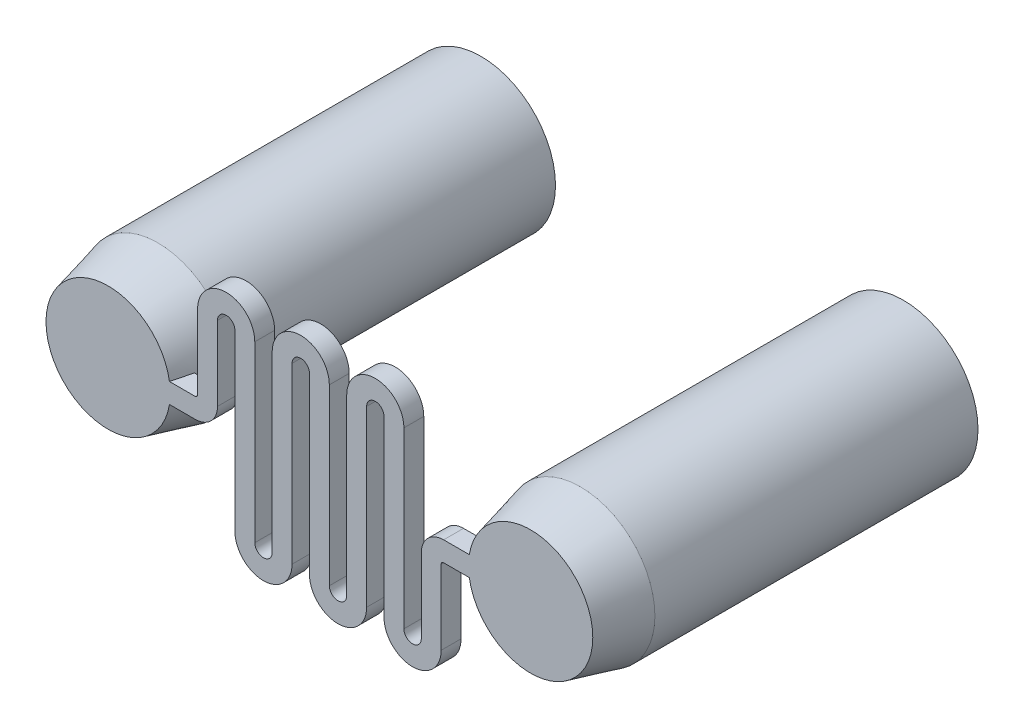
SolidWorks part; units mm, degrees
ref_plane "Front Plane" through (0, 0, 0) normal (0, 0, 1) x (1, 0, 0)
ref_plane "Top Plane" through (0, 0, 0) normal (0, 1, 0) x (1, 0, 0)
ref_plane "Right Plane" through (0, 0, 0) normal (1, 0, 0) x (0, 0, -1)
sketch "Sketch2" plane through (0, 0, 0) normal (0, 0, 1) x (1, 0, 0)
  line L3 (-20.5, -0.8) -> (-13.5, -0.8)
  line L6 (-11.7, 1) -> (-11.7, 7)
  line L9 (-10.3, 7) -> (-10.3, 0)
  line L12 (-10.3, 0) -> (-10.3, -7)
  line L15 (-5.7, -7) -> (-5.7, 0)
  line L18 (-5.7, 0) -> (-5.7, 7)
  line L21 (-4.3, 7) -> (-4.3, 0)
  line L22 (-4.3, 0) -> (-4.3, -7)
  line L23 (0.3, -7) -> (0.3, 0)
  line L24 (0.3, 0) -> (0.3, 7)
  line L25 (1.7, 7) -> (1.7, 0)
  line L26 (1.7, 0) -> (1.7, -7)
  line L27 (6.3, -7) -> (6.3, -1)
  line L28 (6.5, -0.8) -> (13.5, -0.8)
  line L29 (-20.5, 0.8) -> (-13.5, 0.8)
  line L30 (-13.3, 1) -> (-13.3, 7)
  line L31 (-8.7, 7) -> (-8.7, 0)
  line L32 (-8.7, 0) -> (-8.7, -7)
  line L33 (-7.3, -7) -> (-7.3, 0)
  line L34 (-7.3, 0) -> (-7.3, 7)
  line L35 (-2.7, 7) -> (-2.7, 0)
  line L36 (-2.7, 0) -> (-2.7, -7)
  line L37 (-1.3, -7) -> (-1.3, 0)
  line L38 (-1.3, 0) -> (-1.3, 7)
  line L39 (3.3, 7) -> (3.3, 0)
  line L40 (3.3, 0) -> (3.3, -7)
  line L41 (4.7, -7) -> (4.7, -1)
  line L42 (6.5, 0.8) -> (13.5, 0.8)
  arc A8 (-11.7, 1) -> (-13.5, -0.8) centre (-13.5, 1) cw
  arc A9 (-11.7, 7) -> (-10.3, 7) centre (-11, 7) cw
  arc A10 (-10.3, -7) -> (-5.7, -7) centre (-8, -7) ccw
  arc A11 (-5.7, 7) -> (-4.3, 7) centre (-5, 7) cw
  arc A12 (-4.3, -7) -> (0.3, -7) centre (-2, -7) ccw
  arc A13 (0.3, 7) -> (1.7, 7) centre (1, 7) cw
  arc A14 (1.7, -7) -> (6.3, -7) centre (4, -7) ccw
  arc A15 (6.3, -1) -> (6.5, -0.8) centre (6.5, -1) cw
  arc A16 (-13.3, 1) -> (-13.5, 0.8) centre (-13.5, 1) cw
  arc A17 (-13.3, 7) -> (-8.7, 7) centre (-11, 7) cw
  arc A18 (-8.7, -7) -> (-7.3, -7) centre (-8, -7) ccw
  arc A19 (-7.3, 7) -> (-2.7, 7) centre (-5, 7) cw
  arc A20 (-2.7, -7) -> (-1.3, -7) centre (-2, -7) ccw
  arc A21 (-1.3, 7) -> (3.3, 7) centre (1, 7) cw
  arc A22 (3.3, -7) -> (4.7, -7) centre (4, -7) ccw
  arc A23 (4.7, -1) -> (6.5, 0.8) centre (6.5, -1) cw
  arc A24 (-20.5, 0.8) -> (-20.5, -0.8) centre (-20.5, 0) ccw
  arc A25 (13.5, -0.8) -> (13.5, 0.8) centre (13.5, 0) ccw
  point P4 (0, 0)
  point P32 (5.5, 0)
  point P35 (-12.5, 0)
  dimension "D1" = 8
  dimension "D14" = 8
extrude "Boss-Extrude1" add sketch "Sketch2" along normal blind 1.6
ref_plane "Plane1" through (0, 0, 0) normal (0, 1, 0) x (1, 0, 0)
ref_plane "Plane2" through (0, 0, 0) normal (0, 1, 0) x (1, 0, 0)
sketch "Sketch3" plane through (0, 0, 0) normal (0, 1, 0) x (1, 0, 0)
  line L0 (-20.5, -1.6) -> (-25.5, -1.6)
  line L2 (-20.5, -1.6) -> (-20.5, 28.4)
  line L3 (-20.5, 28.4) -> (-26.5, 28.4)
  line L4 (-26.5, 28.4) -> (-26.5, 2.4)
  line L5 (-26.5, 2.4) -> (-25.5, -1.6)
  dimension "D1" = 30
  dimension "D2" = 5
  dimension "D4" = 6
revolve "Revolve1" add sketch "Sketch3" angle 360 about L2
sketch "Sketch4" plane through (0, 0, 0) normal (0, 1, 0) x (1, 0, 0)
  line L0 (13.5, -1.6) -> (18.5, -1.6)
  line L2 (13.5, -1.6) -> (13.5, 28.4)
  line L3 (13.5, 28.4) -> (19.5, 28.4)
  line L4 (19.5, 28.4) -> (19.5, 2.4)
  line L5 (19.5, 2.4) -> (18.5, -1.6)
  dimension "D1" = 5
  dimension "D3" = 30
  dimension "D4" = 6
revolve "Revolve2" add sketch "Sketch4" angle 360 about L2
sketch "Sketch5" plane through (0, 0, -28.4) normal (0, 0, -1) x (-1, 0, 0)
  circle A0 centre (20.5, 0) radius 5
  circle A1 centre (-13.5, 0) radius 5
  dimension "D1" = 10
  dimension "D2" = 10
extrude "Cut-Extrude1" cut sketch "Sketch5" against normal blind 28
